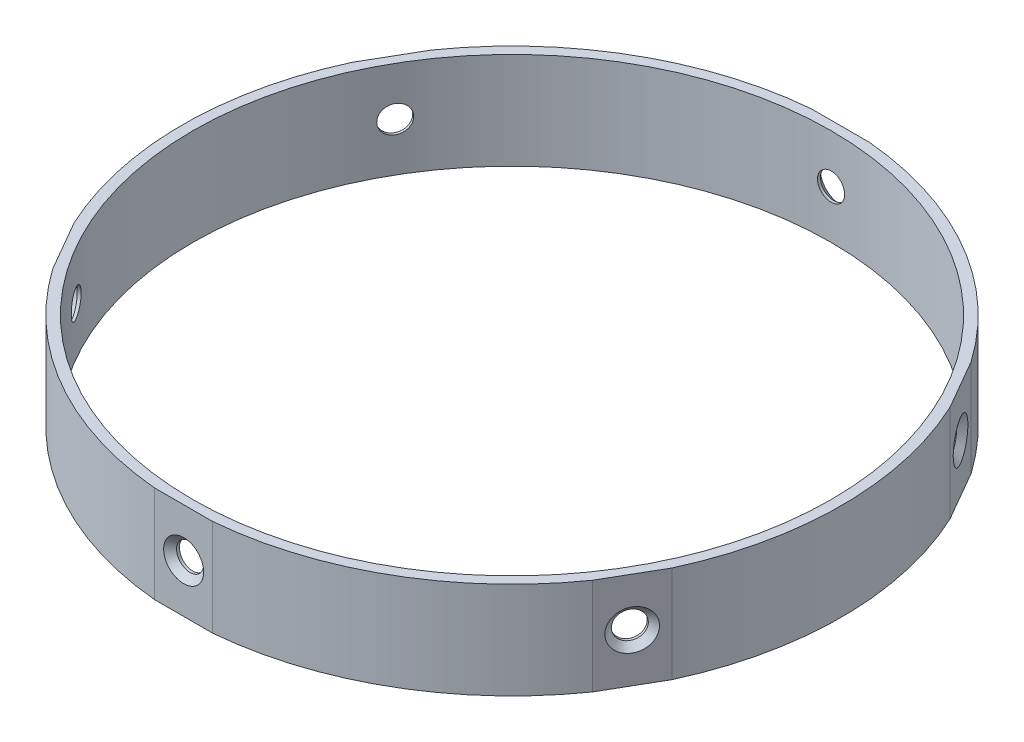
SolidWorks part; units mm, degrees
ref_plane "Спереди" through (0, 0, 0) normal (0, 0, 1) x (1, 0, 0)
ref_plane "Сверху" through (0, 0, 0) normal (0, 1, 0) x (1, 0, 0)
ref_plane "Справа" through (0, 0, 0) normal (1, 0, 0) x (0, 0, -1)
other "Configuration Table"
sketch "Эскиз2" plane through (0, 0, 0) normal (0, 1, 0) x (1, 0, 0)
  circle A0 centre (0, 0) radius 51.1
  circle A1 centre (0, 0) radius 49.5
  dimension "D1" = 99
  dimension "D2" = 1.6
extrude "Бобышка-Вытянуть1" add sketch "Эскиз2" along normal blind 15
sketch "Эскиз4" plane through (0, 0, 0) normal (0, 1, 0) x (1, 0, 0)
  line L0 (0, 0) -> (0, -51.1) construction
  line L1 (-4.5, -51.1) -> (4.5, -51.1)
  line L5 (-4.5, -51.1) -> (-4.5, -50.3894)
  line L6 (-4.5, -50.3894) -> (4.5, -50.3894)
  line L7 (4.5, -50.3894) -> (4.5, -51.1)
  circle A0 centre (0, 0) radius 51.1 construction
  dimension "D2" = 4.5
  dimension "D1" = 9
sketch "Эскиз3" plane through (0, 0, 0) normal (0, 0, 1) x (1, 0, 0)
  circle A0 centre (0, 7.5) radius 2.1
  dimension "D1" = 4.2
  dimension "D2" = 7.5
extrude "Вырез-Вытянуть1" cut sketch "Эскиз3" against normal blind 60
sketch "Эскиз5" plane through (0, 15, 0) normal (0, 1, 0) x (1, 0, 0)
  line L0 (-4.5, -50.9015) -> (4.5, -50.9015)
  line L1 (0, 0) -> (0, -51.1) construction
  circle A0 centre (0, 0) radius 51.1 construction
  arc A1 (-4.5, -50.9015) -> (4.5, -50.9015) centre (0, 0) ccw
  dimension "D1" = 9
extrude "Вырез-Вытянуть2" cut sketch "Эскиз5" against normal blind 15
pattern_circular "Круговой массив4" count 6 over 360 about axis through (0, 0, 0) along (0, 1, 0) of "Вырез-Вытянуть2"
pattern_circular "Круговой массив5" count 6 over 360 about axis through (0, 15, 0) along (0, 1, 0) of "Вырез-Вытянуть1"
chamfer "Фаска1" distance 1 angle 45 6 edges at (2.1, 7.5, -50.9015) (45.132, 7.5, -23.6321) (43.032, 7.5, 27.2694) (-2.1, 7.5, 50.9015) (-45.132, 7.5, 23.6321) (-43.032, 7.5, -27.2694)
